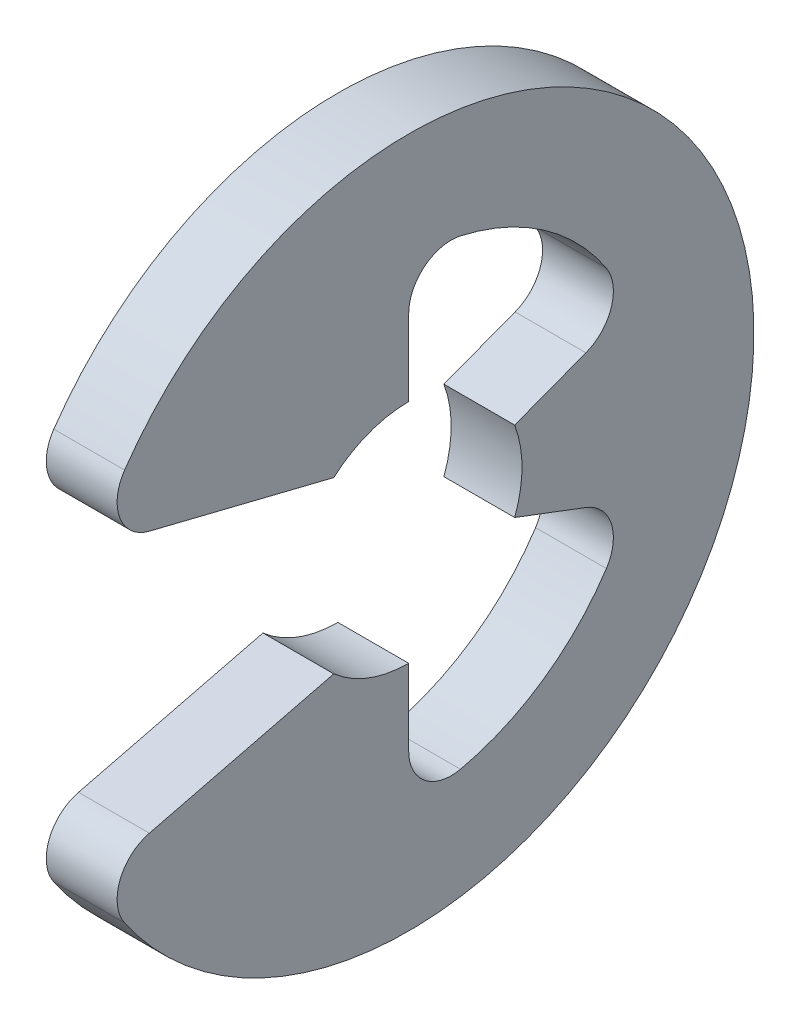
SolidWorks part; units mm, degrees
material "AISI 304"
ref_plane "Front" through (0, 0, 0) normal (0, 0, 1) x (1, 0, 0)
ref_plane "Top" through (0, 0, 0) normal (0, 1, 0) x (1, 0, 0)
ref_plane "Right" through (0, 0, 0) normal (1, 0, 0) x (0, 0, -1)
sketch "Sketch1" plane through (0, 0, 0) normal (1, 0, 0) x (0, 0, -1)
  line L0 (-1.7716, -0.8147) -> (-0.4233, -0.48)
  line L1 (-1.7716, 0.8147) -> (-0.4233, 0.48)
  line L2 (0, -0.64) -> (0, -1.3368)
  line L3 (0, 0.64) -> (0, 1.3368)
  line L4 (0.5987, -0.2263) -> (1.2504, -0.4726)
  line L5 (0.5987, 0.2263) -> (1.2504, 0.4726)
  line L6 (0, 0) -> (-2.125, 0) construction
  line L7 (0.5987, 0.2263) -> (0.5987, -0.2263) construction
  line L8 (0, -0.64) -> (-0.4233, -0.48) construction
  circle A1 centre (0, 0) radius 2.125 construction
  circle A2 centre (0, 0) radius 0.64 construction
  arc A3 (-1.7716, -0.8147) -> (-1.7716, 0.8147) centre (0, 0) ccw
  arc A4 (-0.4233, -0.48) -> (0, -0.64) centre (0, 0) ccw
  arc A5 (-0.4233, 0.48) -> (0, 0.64) centre (0, 0) cw
  arc A6 (0.5987, 0.2263) -> (0.5987, -0.2263) centre (0, 0) cw
  arc A7 (0, -1.3368) -> (1.2504, -0.4726) centre (0, 0) ccw
  arc A8 (1.2504, 0.4726) -> (0, 1.3368) centre (0, 0) ccw
  dimension "D" = 1.28
  dimension "D1" = 1.3368
  dimension "OD" = 3.9
  dimension "D2" = 0.7277
  dimension "D3" = 0.96
extrude "Extrude1" add sketch "Sketch1" along normal mid plane 0.4
fillet "Fillet1" radius 0.24 6 edges at (0, -1.3368, 0) (0, 1.3368, 0) (0, -0.8147, 1.7716) (0, 0.8147, 1.7716) (0, -0.4726, -1.2504) (0, 0.4726, -1.2504)
sketch "Sketch3" plane through (0, 0, 0) normal (0, 1, 0) x (1, 0, 0)
  line L0 (0.22, 1) -> (0.22, 0.75)
  line L1 (0.22, 0.75) -> (-0.22, 0.75)
  line L2 (-0.22, 0.75) -> (-0.22, 1)
  line L3 (-0.22, 1) -> (-3.08, 1)
  line L4 (1.32, 0) -> (1.32, 0.875)
  line L5 (-3.08, 1) -> (-3.08, 0)
  line L6 (-3.08, 0) -> (1.32, 0)
  line L8 (1.32, 0) -> (1.32, 1) construction
  line L9 (1.32, 1) -> (0.22, 1) construction
  line L10 (1.32, 0) -> (17.2631, 0) construction
  line L11 (1.32, 0.875) -> (1.195, 1)
  line L12 (1.195, 1) -> (0.22, 1)
  point P2 (0, 0.75)
  point P5 (0.22, 0.875)
  dimension "D2" = 4.4
  dimension "D1" = 1.1
  dimension "D3" = 45
revolve "Revolve2" [suppressed] add sketch "Sketch3" angle 360 about L10
equation "\"D2@Sketch3\" = \"W@Sketch3\"*10"
equation "\"D1@Sketch3\" = \"D2@Sketch3\"/4"
equation "\"D1@Sketch1\" = (\"OD@Sketch1\"+\"D@Sketch1\")/3.875"
equation "\"D3@Sketch1\" = \"D@Sketch1\"*.75"
equation "\"D1@Fillet1\" = \"D1@Extrude1\"*.6"
